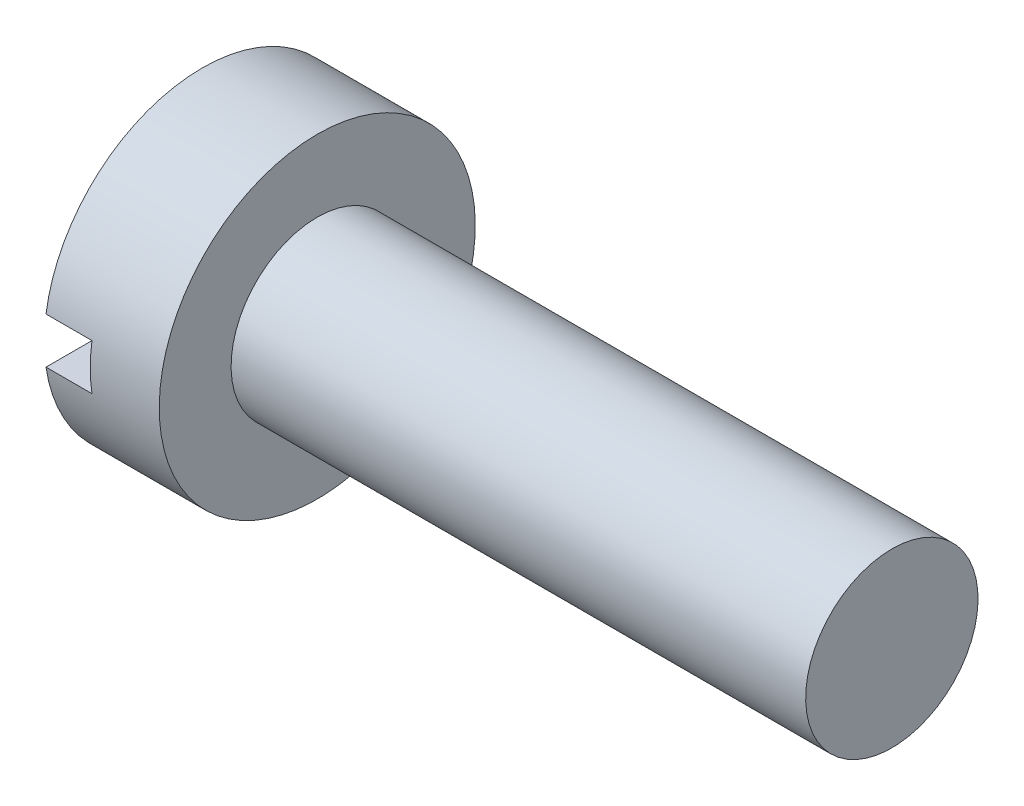
SolidWorks part; units mm, degrees
material "Plain Carbon Steel"
ref_plane "Front Plane" through (0, 0, 0) normal (0, 0, 1) x (1, 0, 0)
ref_plane "Top Plane" through (0, 0, 0) normal (0, 1, 0) x (1, 0, 0)
ref_plane "Right Plane" through (0, 0, 0) normal (1, 0, 0) x (0, 0, -1)
sketch "Sketch1" plane through (0, 0, 0) normal (0, 0, 1) x (1, 0, 0)
  line L0 (0, 0) -> (0, 2.75)
  line L1 (0, 2.75) -> (2, 2.75)
  line L2 (2, 2.75) -> (2, 1.5)
  line L3 (2, 1.5) -> (12, 1.5)
  line L4 (12, 1.5) -> (12, 0)
  line L5 (12, 0) -> (0, 0) construction
  line L6 (0, 0) -> (12, 0)
  dimension "D1" = 3
  dimension "D2" = 10
  dimension "D3" = 5.5
  dimension "D4" = 2
revolve "Revolve1" add sketch "Sketch1" angle 360 about L5
sketch "Sketch2" plane through (0, 0, 0) normal (-1, 0, 0) x (0, 0, 1)
  line L0 (2.75, 0) -> (-2.75, 0) construction
  line L1 (-2.75, 0.4) -> (2.75, 0.4)
  line L2 (-2.75, 0.4) -> (-2.75, -0.4)
  line L3 (-2.75, -0.4) -> (2.75, -0.4)
  line L4 (2.75, 0.4) -> (2.75, -0.4)
  circle A0 centre (0, 0) radius 2.75 construction
  dimension "D1" = 0.8
extrude "Cut-Extrude1" cut sketch "Sketch2" against normal blind 0.8
